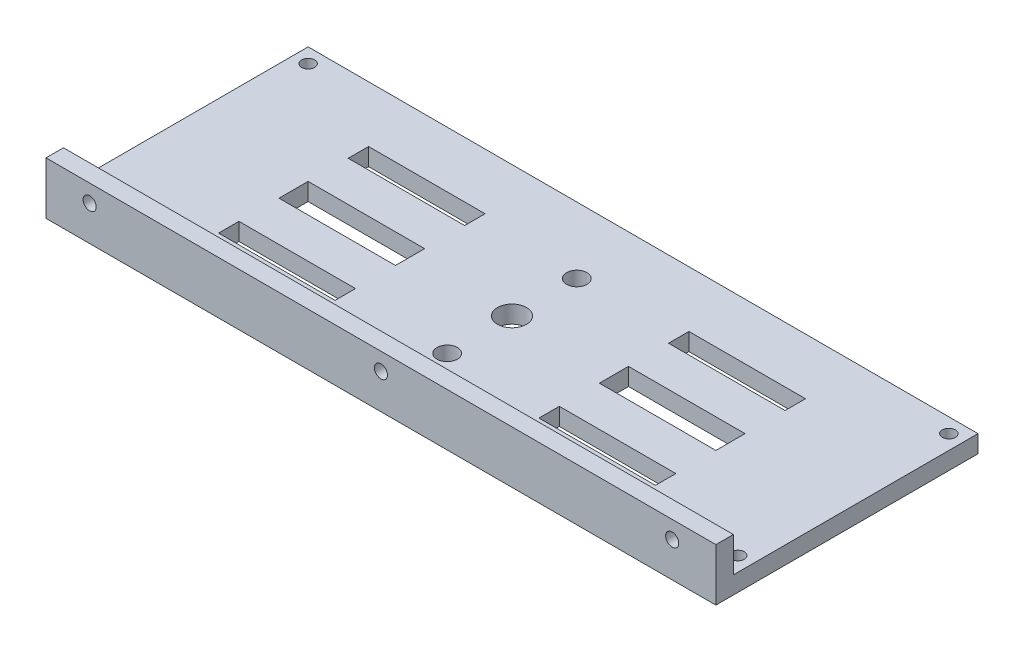
SolidWorks part; units mm, degrees
ref_plane "Front Plane" through (0, 0, 0) normal (0, 0, 1) x (1, 0, 0)
ref_plane "Top Plane" through (0, 0, 0) normal (0, 1, 0) x (1, 0, 0)
ref_plane "Right Plane" through (0, 0, 0) normal (1, 0, 0) x (0, 0, -1)
sketch "Sketch1" plane through (0, 0, 0) normal (0, 1, 0) x (1, 0, 0)
  line L0 (0, 0) -> (0, 22.25) construction
  line L1 (-115, 45) -> (115, 45)
  line L2 (-115, 45) -> (-115, -45)
  line L3 (-115, -45) -> (115, -45)
  line L4 (115, 45) -> (115, -45)
  line L5 (0, 0) -> (-19.3489, 0) construction
  line L6 (0, -5) -> (0, 5) construction
  line L7 (35, 5) -> (75, 5)
  line L8 (35, 5) -> (35, -5)
  line L9 (35, -5) -> (75, -5)
  line L10 (75, 5) -> (75, -5)
  line L11 (0, 25.75) -> (0, 18.75) construction
  line L12 (35, 18.75) -> (75, 18.75)
  line L13 (35, 18.75) -> (35, 25.75)
  line L14 (35, 25.75) -> (75, 25.75)
  line L15 (75, 18.75) -> (75, 25.75)
  line L16 (35, -25.75) -> (75, -25.75)
  line L17 (75, -18.75) -> (75, -25.75)
  line L18 (35, -18.75) -> (75, -18.75)
  line L19 (35, -18.75) -> (35, -25.75)
  line L20 (-35, -18.75) -> (-35, -25.75)
  line L21 (-35, -18.75) -> (-75, -18.75)
  line L22 (-75, -18.75) -> (-75, -25.75)
  line L23 (-35, -25.75) -> (-75, -25.75)
  line L24 (-35, -5) -> (-75, -5)
  line L25 (-75, 5) -> (-75, -5)
  line L26 (-35, 5) -> (-75, 5)
  line L27 (-35, 5) -> (-35, -5)
  line L28 (-35, 25.75) -> (-75, 25.75)
  line L29 (-75, 18.75) -> (-75, 25.75)
  line L30 (-35, 18.75) -> (-75, 18.75)
  line L31 (-35, 18.75) -> (-35, 25.75)
  line L32 (110, 40) -> (110, 45) construction
  line L33 (110, 40) -> (115, 40) construction
  line L34 (110, -32.5) -> (110, -45) construction
  line L35 (110, -32.5) -> (115, -32.5) construction
  circle A0 centre (0, 0) radius 5
  circle A1 centre (0, 22.25) radius 3.5
  circle A2 centre (0, -22.25) radius 3.5
  circle A3 centre (110, 40) radius 2.25
  circle A4 centre (110, -32.5) radius 2.25
  circle A5 centre (-110, 40) radius 2.25
  circle A6 centre (-110, -32.5) radius 2.25
  point P4 (0, 45)
  point P6 (115, 0)
  point P21 (35, 0)
  point P28 (35, 22.25)
  dimension "D3" = 10
  dimension "D5" = 7
  dimension "D9" = 4.5
  dimension "D1" = 90
  dimension "D2" = 230
  dimension "D4" = 22.25
  dimension "D6" = 75
  dimension "D7" = 35
  dimension "D8" = 5
  dimension "D10" = 12.5
extrude "Boss-Extrude1" add sketch "Sketch1" along normal blind 6
ref_plane "Plane1" through (0, 6, 0) normal (0, 1, 0) x (1, 0, 0)
sketch "Sketch2" plane through (0, 6, 0) normal (0, 1, 0) x (1, 0, 0)
  line L1 (-115, -39) -> (115, -39)
  line L2 (-115, -39) -> (-115, -45)
  line L3 (-115, -45) -> (115, -45)
  line L4 (115, -39) -> (115, -45)
  line L5 (-115, -45) -> (115, -45) construction
  line L6 (-115, 45) -> (-115, -45) construction
  line L7 (-115, 45) -> (-115, -45) construction
  line L8 (-115, -45) -> (115, -45) construction
  point P4 (0, -45)
  point P6 (0, -45)
  dimension "D1" = 6
extrude "Boss-Extrude2" add sketch "Sketch2" along normal blind 12
ref_plane "Plane2" through (0, 0, 39) normal (0, 0, -1) x (-1, 0, 0)
sketch "Sketch3" plane through (0, 0, 39) normal (0, 0, -1) x (-1, 0, 0)
  line L0 (-115, 18) -> (-115, 6) construction
  line L1 (-115, 18) -> (-115, 6) construction
  circle A0 centre (0, 12) radius 2.25
  circle A1 centre (100, 12) radius 2.25
  circle A2 centre (-100, 12) radius 2.25
  point P4 (-115, 12)
  dimension "D1" = 4.5
  dimension "D2" = 2
  dimension "D3" = 2
extrude "Cut-Extrude1" cut sketch "Sketch3" against normal up to next
